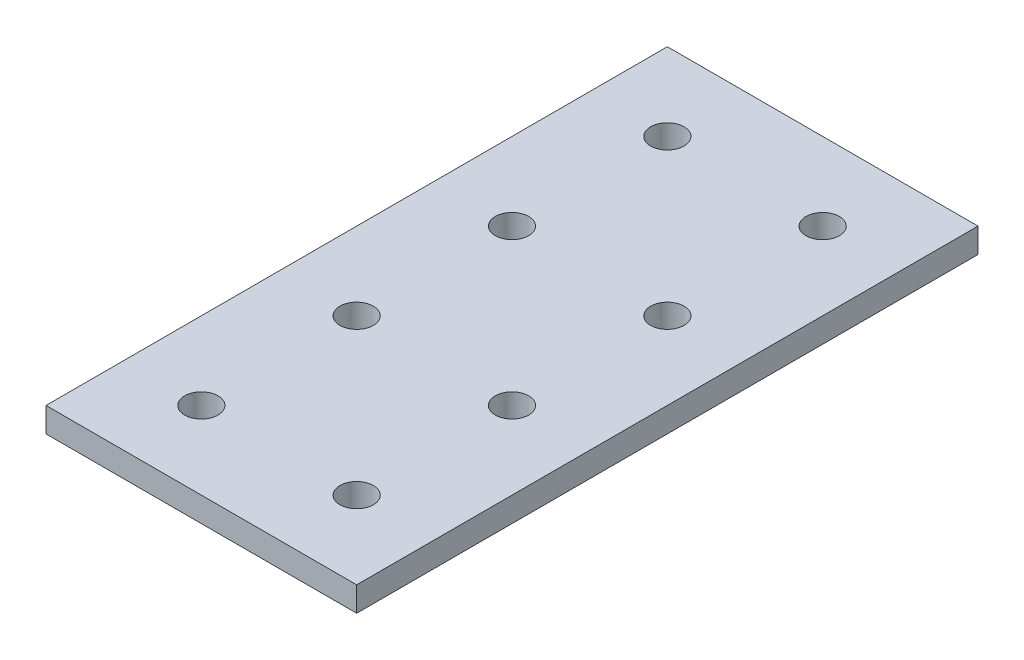
SolidWorks part; units mm, degrees
material "6061 Alloy"
ref_plane "Front Plane" through (0, 0, 0) normal (0, 0, 1) x (1, 0, 0)
ref_plane "Top Plane" through (0, 0, 0) normal (0, 1, 0) x (1, 0, 0)
ref_plane "Right Plane" through (0, 0, 0) normal (1, 0, 0) x (0, 0, -1)
sketch "Sketch1" plane through (0, 0, 0) normal (0, 1, 0) x (1, 0, 0)
  line L1 (0, 0) -> (40, 0)
  line L2 (0, 0) -> (0, 80)
  line L3 (0, 80) -> (40, 80)
  line L4 (40, 0) -> (40, 80)
  dimension "D1" = 40
  dimension "D2" = 80
extrude "Boss-Extrude1" add sketch "Sketch1" along normal blind 3.175
sketch "Sketch2" plane through (0, 3.175, 0) normal (0, 1, 0) x (1, 0, 0)
  line L0 (0, 80) -> (0, 0) construction
  line L1 (40, 80) -> (0, 80) construction
  line L2 (10, 70) -> (30, 70) construction
  line L3 (10, 70) -> (10, 50) construction
  point P0 (10, 70)
  point P7 (30, 70)
  point P8 (30, 50)
  point P9 (30, 30)
  point P10 (30, 10)
  point P11 (10, 50)
  point P12 (10, 30)
  point P13 (10, 10)
  dimension "D1" = 10
  dimension "D2" = 10
  dimension "D5" = 20
  dimension "D6" = 20
  dimension "D3" = 2
  dimension "D4" = 4
hole_wizard "M4 Clearance Hole1" positions "Sketch2" profile "Sketch3" hole size "M4" standard "ANSI Metric" end condition through all
sketch "Sketch3" plane through (10, 3.175, -70) normal (1, 0, 0) x (0, 0, 1)
  line L0 (0, 0) -> (0, 3.175)
  line L1 (0, 3.175) -> (2.15, 3.175)
  line L2 (2.15, 3.175) -> (2.15, 0)
  line L5 (2.15, 0) -> (0, 0)
  line L11 (0, -6.35) -> (0, 107.95) construction
  dimension "Thru Hole Dia." = 4.3
  dimension "Thru Hole Depth" = 3.175
